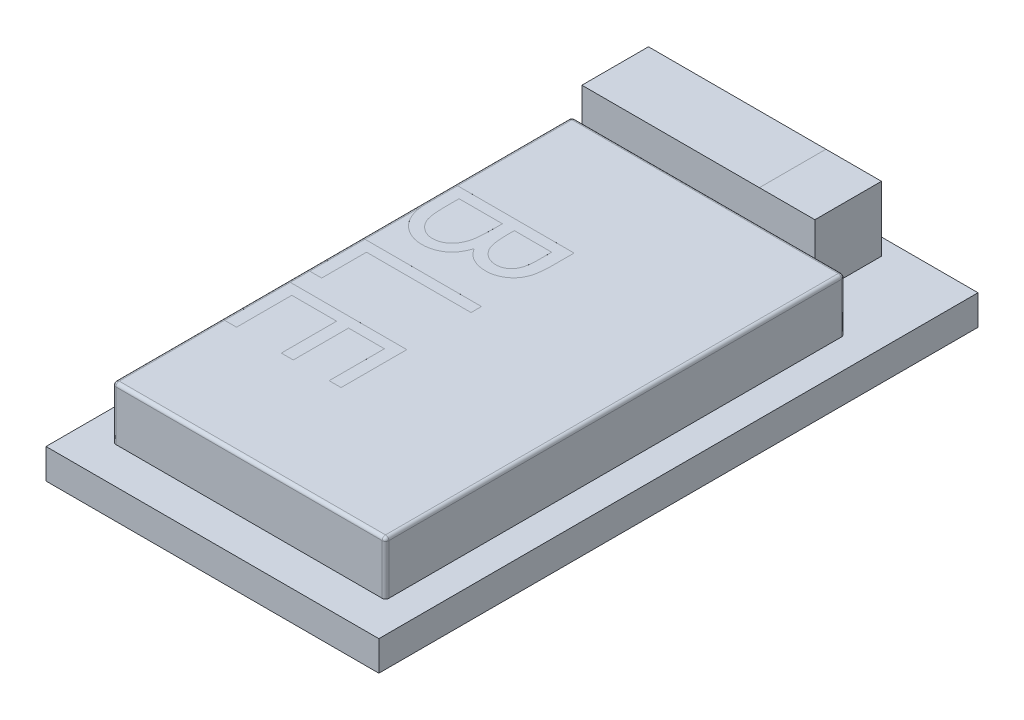
SolidWorks part; units mm, degrees
ref_plane "Piano frontale" through (0, 0, 0) normal (0, 0, 1) x (1, 0, 0)
ref_plane "Piano superiore" through (0, 0, 0) normal (0, 1, 0) x (1, 0, 0)
ref_plane "Piano destro" through (0, 0, 0) normal (1, 0, 0) x (0, 0, -1)
sketch "Schizzo1" plane through (0, 0, 0) normal (0, 1, 0) x (1, 0, 0)
  line L1 (-13.2216, 30.1798) -> (-3.2216, 30.1798)
  line L2 (-13.2216, 30.1798) -> (-13.2216, 12.1798)
  line L3 (-13.2216, 12.1798) -> (-3.2216, 12.1798)
  line L4 (-3.2216, 30.1798) -> (-3.2216, 12.1798)
  dimension "D1" = 10
  dimension "D2" = 18
extrude "Estrusione-Estrusione1" add sketch "Schizzo1" along normal blind 0.9
sketch "Schizzo2" plane through (0, 0.9, 0) normal (0, 1, 0) x (1, 0, 0)
  line L0 (-13.2216, 30.1798) -> (-13.2216, 12.1798) construction
  line L1 (-12.3216, 27.0798) -> (-4.1216, 27.0798)
  line L2 (-12.3216, 27.0798) -> (-12.3216, 13.2798)
  line L3 (-12.3216, 13.2798) -> (-4.1216, 13.2798)
  line L4 (-4.1216, 27.0798) -> (-4.1216, 13.2798)
  line L7 (-13.2216, 12.1798) -> (-3.2216, 12.1798) construction
  dimension "D1" = 8.2
  dimension "D2" = 13.8
  dimension "D3" = 0.9
  dimension "D4" = 1.1
extrude "Estrusione-Estrusione2" add sketch "Schizzo2" along normal blind 1.6
fillet "Raccordo1" radius 0.1 8 edges at (-8.2216, 2.5, -27.0798) (-12.3216, 2.5, -20.1798) (-8.2216, 2.5, -13.2798) (-4.1216, 2.5, -20.1798) (-4.1216, 1.7, -27.0798) (-12.3216, 1.7, -27.0798) (-4.1216, 1.7, -13.2798) (-12.3216, 1.7, -13.2798)
sketch "Schizzo3" plane through (0, 0.9, 0) normal (0, 1, 0) x (1, 0, 0)
  line L0 (-13.2216, 30.1798) -> (-13.2216, 12.1798) construction
  line L1 (-12.6216, 29.6798) -> (-5.6216, 29.6798)
  line L2 (-12.6216, 29.6798) -> (-12.6216, 27.6798)
  line L3 (-12.6216, 27.6798) -> (-5.6216, 27.6798)
  line L4 (-5.6216, 29.6798) -> (-5.6216, 27.6798)
  line L6 (-3.2216, 30.1798) -> (-13.2216, 30.1798) construction
  dimension "D1" = 2
  dimension "D2" = 7
  dimension "D3" = 0.6
  dimension "D4" = 0.5
extrude "Estrusione-Estrusione3" add sketch "Schizzo3" along normal blind 1.95
sketch "Schizzo4" plane through (0, 2.85, 0) normal (0, 1, 0) x (1, 0, 0)
  line L0 (-12.6216, 27.6798) -> (-5.6216, 27.6798) construction
  line L1 (-5.6216, 29.6798) -> (-7.2897, 29.6798)
  line L2 (-5.6216, 29.6798) -> (-5.6216, 27.6798)
  line L3 (-5.6216, 27.6798) -> (-7.2897, 27.6798)
  line L4 (-7.2897, 29.6798) -> (-7.2897, 27.6798)
extrude "Estrusione-Estrusione4" add sketch "Schizzo4" along normal blind 0.0001
sketch "Schizzo6" plane through (0, 2.5, 0) normal (0, 1, 0) x (1, 0, 0)
  text T0 "BLE"
extrude "Taglio-Estrusione1" cut sketch "Schizzo6" against normal blind 0.0001
